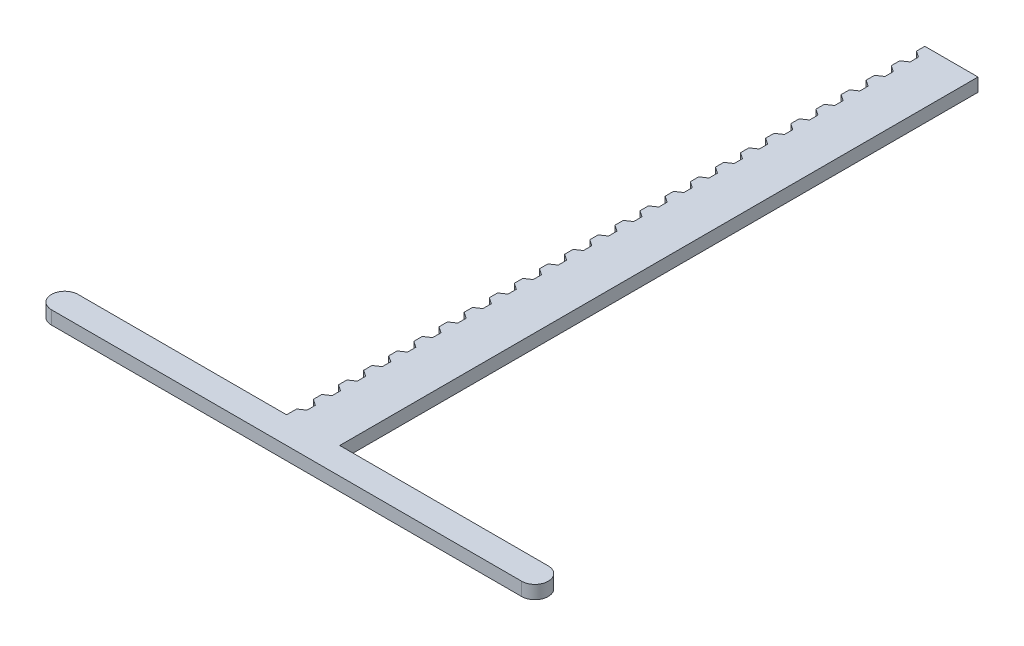
SolidWorks part; units mm, degrees
ref_plane "Front Plane" through (0, 0, 0) normal (0, 0, 1) x (1, 0, 0)
ref_plane "Top Plane" through (0, 0, 0) normal (0, 1, 0) x (1, 0, 0)
ref_plane "Right Plane" through (0, 0, 0) normal (1, 0, 0) x (0, 0, -1)
sketch "Sketch1" plane through (0, 0, 0) normal (0, 1, 0) x (1, 0, 0)
  line L0 (-6.35, 0) -> (-56.134, 0)
  line L1 (-6.35, 152.4) -> (6.35, 152.4)
  line L2 (-6.35, 152.4) -> (-6.35, 0)
  line L4 (6.35, 152.4) -> (6.35, 0)
  line L5 (56.134, 0) -> (6.35, 0)
  line L7 (56.134, -6.35) -> (-56.134, -6.35)
  arc A0 (-56.134, 0) -> (-56.134, -6.35) centre (-56.134, -3.175) ccw
  arc A1 (56.134, -6.35) -> (56.134, 0) centre (56.134, -3.175) ccw
  dimension "D4" = 6.35
  dimension "D5" = 6.35
  dimension "D2" = 12.7
  dimension "D3" = 6.35
extrude "Boss-Extrude1" add sketch "Sketch1" along normal blind 3.175
sketch "Sketch2" plane through (0, 3.175, 0) normal (0, 1, 0) x (1, 0, 0)
  line L0 (-6.35, 150.4) -> (-4.8695, 149.4)
  line L1 (-6.35, 152.4) -> (-6.35, 0) construction
  line L2 (-4.8695, 149.4) -> (-4.8695, 147.4)
  line L3 (-4.8695, 147.4) -> (-6.35, 146.4)
  line L4 (-6.35, 146.4) -> (-6.35, 150.4)
  line L5 (-6.35, 150.4) -> (6.35, 150.4) construction
  line L6 (6.35, 0) -> (6.35, 152.4) construction
  line L7 (-6.35, 146.4) -> (6.35, 146.4) construction
  line L8 (-4.8695, 149.4) -> (6.35, 149.4) construction
  line L9 (-4.8695, 147.4) -> (6.35, 147.4) construction
  line L10 (6.35, 152.4) -> (-6.35, 152.4) construction
  dimension "D1" = 2
  dimension "D2" = 1
  dimension "D3" = 1
  dimension "D4" = 2
extrude "Cut-Extrude1" cut sketch "Sketch2" against normal blind 3.175
pattern_linear "LPattern1" count 25 spacing 6 along (0, 0, 1) of "Cut-Extrude1"
